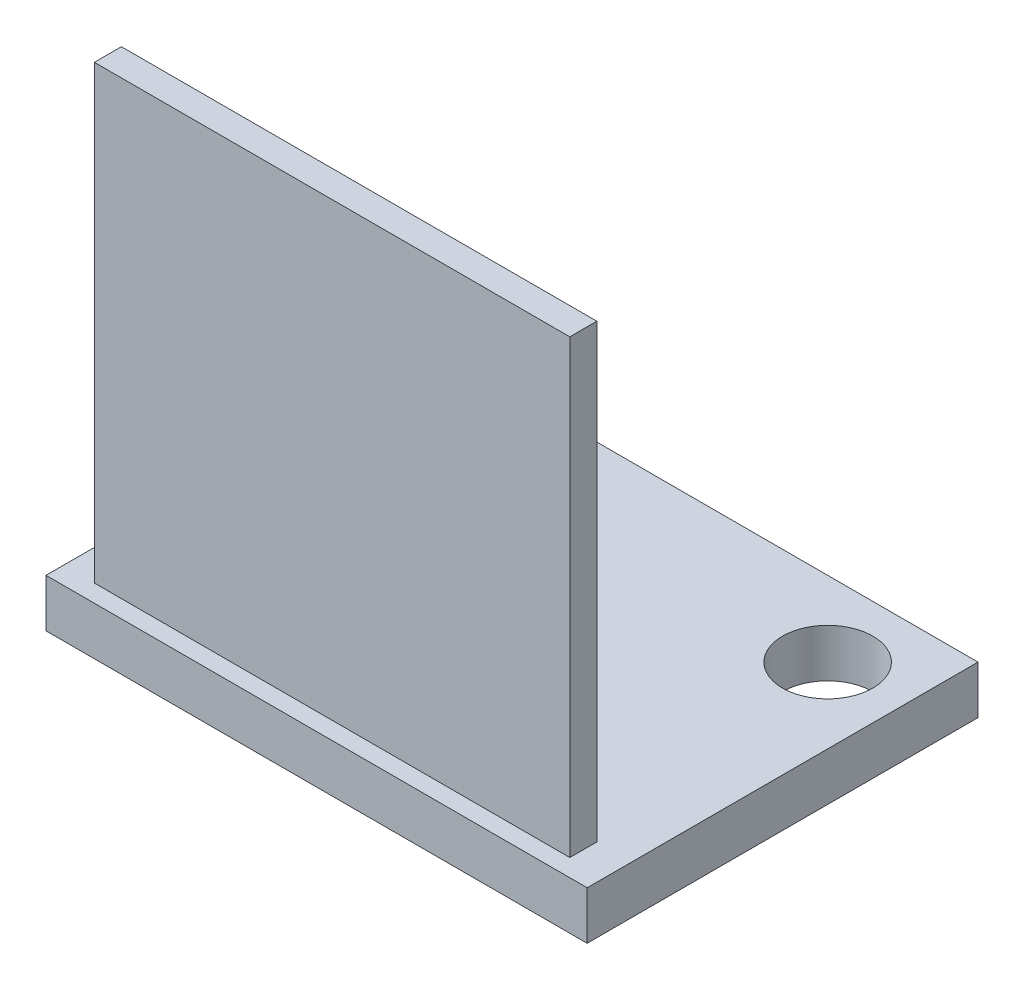
SolidWorks part; units mm, degrees
ref_plane "前视基准面" through (0, 0, 0) normal (0, 0, 1) x (1, 0, 0)
ref_plane "上视基准面" through (0, 0, 0) normal (0, 1, 0) x (1, 0, 0)
ref_plane "右视基准面" through (0, 0, 0) normal (1, 0, 0) x (0, 0, -1)
other "Configuration Table"
sketch "草图1" plane through (0, 0, 0) normal (0, 1, 0) x (1, 0, 0)
  line L1 (0, 0) -> (18, 0)
  line L2 (0, 0) -> (0, -13)
  line L3 (0, -13) -> (18, -13)
  line L4 (18, 0) -> (18, -13)
  circle A0 centre (2.5, -2.5) radius 1.5
  circle A1 centre (15.5, -2.5) radius 1.5
  point P11 (13.9418, 0)
  dimension "D3" = 3
  dimension "D4" = 3
  dimension "D1" = 18
  dimension "D2" = 13
  dimension "D5" = 13
  dimension "D6" = 2.5
  dimension "D7" = 2.5
extrude "凸台-拉伸1" add sketch "草图1" along normal blind 1.6
sketch "草图2" plane through (0, 0, 0) normal (0, -1, 0) x (1, 0, 0)
  line L0 (0, 0) -> (0, 13) construction
  line L1 (1.5, 12) -> (16.5, 12)
  line L2 (1.5, 12) -> (1.5, 10.5)
  line L3 (1.5, 10.5) -> (16.5, 10.5)
  line L4 (16.5, 12) -> (16.5, 10.5)
  line L5 (18, 13) -> (18, 0) construction
  line L6 (0, 13) -> (18, 13) construction
  dimension "D1" = 1.5
  dimension "D2" = 1.5
  dimension "D3" = 1
  dimension "D4" = 1.5
extrude "凸台-拉伸2" add sketch "草图2" along normal blind 1
sketch "草图3" plane through (0, 1.6, 0) normal (0, 1, 0) x (1, 0, 0)
  line L1 (1.0263, -11.5189) -> (16.8405, -11.5189)
  line L2 (1.0263, -11.5189) -> (1.0263, -12.4178)
  line L3 (1.0263, -12.4178) -> (16.8405, -12.4178)
  line L4 (16.8405, -11.5189) -> (16.8405, -12.4178)
extrude "凸台-拉伸3" add sketch "草图3" along normal blind 15
